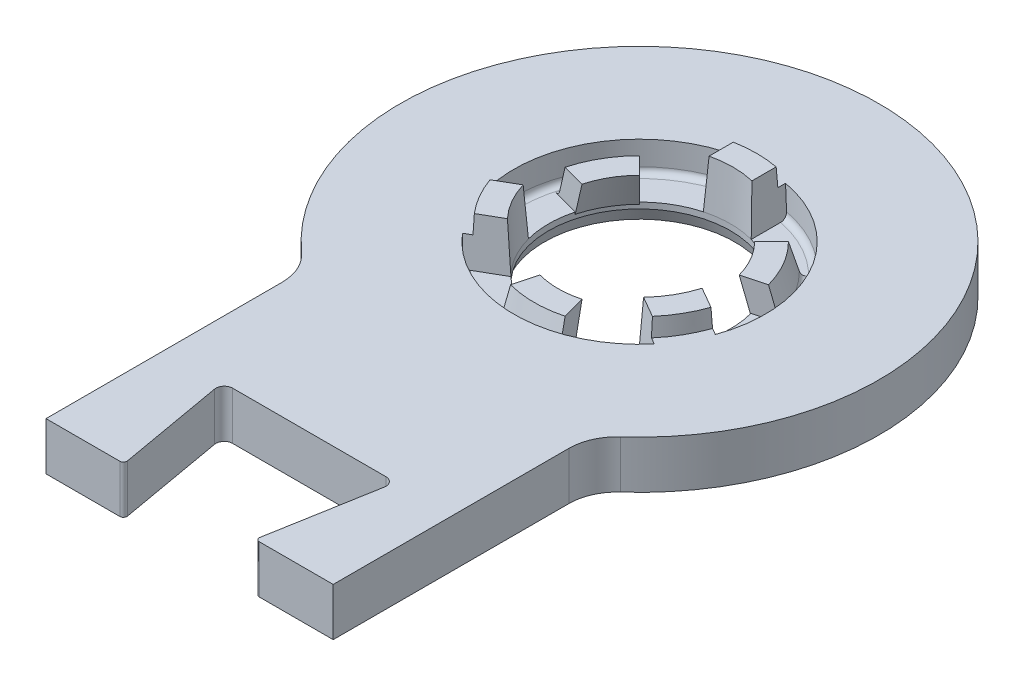
SolidWorks part; units mm, degrees
ref_plane "Front Plane" through (0, 0, 0) normal (0, 0, 1) x (1, 0, 0)
ref_plane "Top Plane" through (0, 0, 0) normal (0, 1, 0) x (1, 0, 0)
ref_plane "Right Plane" through (0, 0, 0) normal (1, 0, 0) x (0, 0, -1)
sketch "Sketch1" plane through (0, 0, 0) normal (0, 1, 0) x (1, 0, 0)
  line L0 (-6, 6) -> (-6, -13.2915)
  line L1 (-6, -19) -> (-2.7023, -19)
  line L2 (6, -19) -> (6, -13.2915)
  line L3 (6, 6) -> (-6, 6)
  line L4 (-6, -13.2915) -> (-6, -19)
  line L5 (6, -13.2915) -> (6, 6)
  line L6 (0, -19) -> (0, 0) construction
  line L7 (-2.6007, -19) -> (-3.5, -13.9) construction
  line L8 (-3.5, -13.9) -> (0, -13.9) construction
  line L9 (-2.7023, -19) -> (-3.6192, -13.8)
  line L10 (-3.6192, -13.8) -> (0, -13.8)
  line L11 (-2.6992, -19.0174) -> (-3.6192, -13.8) construction
  line L12 (2.7023, -19) -> (6, -19)
  line L13 (3.6192, -13.8) -> (0, -13.8)
  line L14 (2.7023, -19) -> (3.6192, -13.8)
  circle A0 centre (0, 0) radius 4
  dimension "D1" = 8
  dimension "D5" = 6
  dimension "D7" = 80
  dimension "D2" = 25
  dimension "D3" = 6
  dimension "D4" = 12
  dimension "D8" = 3.5
  dimension "D9" = 5.1
  dimension "D10" = 0.1
extrude "Boss-Extrude1" add sketch "Sketch1" along normal blind 2
sketch "Sketch2" plane through (0, 0, 0) normal (0, 1, 0) x (1, 0, 0)
  circle A0 centre (0, 0) radius 10
  circle A1 centre (0, 0) radius 3.8
  dimension "D1" = 20
  dimension "D2" = 7.6
extrude "Boss-Extrude2" add sketch "Sketch2" along normal blind 2
sketch "Sketch3" plane through (0, 0, 0) normal (0, -1, 0) x (1, 0, 0)
  line L0 (-3, 0) -> (-3, 4)
  line L1 (3, 0) -> (3, 4)
  arc A0 (-3, 0) -> (3, 0) centre (0, 0) ccw
  arc A1 (-3, 4) -> (3, 4) centre (0, 0) ccw
extrude "Boss-Extrude3" [suppressed] add sketch "Sketch3" along normal blind 4
fillet "Fillet1" [suppressed] radius 0.5
fillet "Fillet2" [suppressed] radius 1
sketch "Sketch4" plane through (0, 2, 0) normal (0, 1, 0) x (1, 0, 0)
  line L0 (-6, -8) -> (-6, -19) construction
  line L1 (-6, -18.8) -> (6, -18.8)
  line L2 (-6, -18.8) -> (-6, -19)
  line L3 (-6, -19) -> (6, -19)
  line L4 (6, -18.8) -> (6, -19)
  dimension "D1" = 0.2
extrude "Cut-Extrude1" cut sketch "Sketch4" against normal blind 4
fillet "Fillet3" radius 0.35 2 edges at (3.6192, 1, 13.8) (-3.6192, 1, 13.8)
fillet "Fillet4" radius 0.15 2 edges at (2.7375, 1, 18.8) (-2.7375, 1, 18.8)
sketch "Sketch5" plane through (0, 0, 0) normal (0, 1, 0) x (1, 0, 0)
  circle A1 centre (0, 0) radius 3
  circle A2 centre (0, 0) radius 2.1
  dimension "D1" = 4.2
  dimension "D2" = 6
extrude "Boss-Extrude4" [suppressed] add sketch "Sketch5" along normal blind 13
fillet "Fillet5" [suppressed] radius 2
fillet "Fillet6" radius 2 2 edges at (-6, 1, 8) (6, 1, 8)
sketch "Sketch6" plane through (0, 2, 0) normal (0, 1, 0) x (1, 0, 0)
  circle A0 centre (0, 0) radius 3.5
  dimension "D1" = 7
extrude "Boss-Extrude5" [suppressed] add sketch "Sketch6" along normal blind 2 contours A0
sketch "Sketch7" [suppressed] plane through (0, 4, 0) normal (0, 1, 0) x (1, 0, 0)
  circle A0 centre (0, 0) radius 3.15
extrude "Cut-Extrude3" [suppressed] cut sketch "Sketch7" against normal blind 3.2
fillet "Fillet7" [suppressed] radius 2
fillet "Fillet8" [suppressed] radius 1
fillet "Fillet9" [suppressed] radius 0.1
sketch "Sketch8" plane through (0, 2, 0) normal (0, 1, 0) x (1, 0, 0)
  line L0 (0, 0) -> (0, 3.9) construction
  line L1 (-0.5, 3.65) -> (0, 2.65)
  line L2 (-0.5, 4.15) -> (0.5, 4.15)
  line L3 (-0.5, 4.15) -> (-0.5, 3.65)
  line L4 (-0.5, 3.65) -> (0.5, 3.65) construction
  line L5 (0.5, 4.15) -> (0.5, 3.65)
  line L6 (-0.5, 4.15) -> (0.5, 3.65) construction
  line L7 (-0.5, 3.65) -> (0.5, 4.15) construction
  line L8 (0, 2.65) -> (0.5, 3.65)
  dimension "D1" = 3.9
  dimension "D2" = 0.5
  dimension "D3" = 1
  dimension "D4" = 1
extrude "Boss-Extrude6" [suppressed] add sketch "Sketch8" against normal blind 2
pattern_circular "CirPattern1" [suppressed] count 5 over 360
sketch "Sketch11" plane through (0, 2, 0) normal (0, 1, 0) x (1, 0, 0)
  circle A0 centre (0, 0) radius 4
  circle A1 centre (0, 0) radius 5
  dimension "D1" = 8
  dimension "D2" = 10
extrude "Boss-Extrude7" [suppressed] add sketch "Sketch11" along normal blind 2 draft 3
sketch "Sketch13" plane through (0, 2, 0) normal (0, 1, 0) x (1, 0, 0)
  circle A0 centre (0, 0) radius 5 construction
  circle A1 centre (0, 0) radius 5.25
  dimension "D1" = 10
  dimension "D2" = 10.5
extrude "Cut-Extrude5" cut sketch "Sketch13" against normal blind 1.25
fillet "Fillet10" [suppressed] radius 0.2
sketch "Sketch12" plane through (0, 0, 0) normal (1, 0, 0) x (0, 0, -1)
  line L0 (0, 0) -> (-4, 0) construction
  line L1 (-7.4536, 0) -> (10, 0) construction
  line L2 (-3.8, 0) -> (3.8, 0) construction
  line L3 (0, 0) -> (0, 2) construction
  line L4 (3.8, 2) -> (-3.8, 2) construction
  line L5 (-4, 0) -> (-3.4, 2)
  line L6 (-3.4, 2) -> (-4.4, 2)
  line L7 (-4.4, 2) -> (-5, 0)
  line L8 (-5, 0) -> (-4, 0)
  line L9 (-4, 0) -> (-4.0344, -0.0135)
  dimension "D1" = 0
  dimension "D2" = 3.4
  dimension "D3" = 1
  dimension "D4" = 4
revolve "Revolve2" add sketch "Sketch12" angle 30 mid plane about L3
pattern_circular "CirPattern2" count 3 over 360 about axis through (0, 0, 0) along (0, 1, 0) of "Revolve2"
chamfer "Chamfer1" distance 0.5 angle 20 1 edges at (0, 0, 3.8)
fillet "Fillet13" [suppressed] radius 0.25
fillet "Fillet14" radius 0.25 4 edges at (0, 0.75, 5.25) (-4.1353, 0.75, -2.3875) (4.1353, 0.75, -2.3875) (0, 0.75, 4.775)
sketch "Sketch15" plane through (0, 0, 0) normal (0, -1, 0) x (1, 0, 0)
  line L2 (1, -4.899) -> (1, -3.6661)
  line L4 (-1, -4.899) -> (-1, -3.6661)
  arc A0 (-1, -3.6661) -> (1, -3.6661) centre (0, 0) ccw
  arc A1 (-1, -4.899) -> (1, -4.899) centre (0, 0) ccw
  point P4 (0, -5)
  dimension "D1" = 7.6
  dimension "D2" = 10
  dimension "D3" = 1
  dimension "D4" = 1
extrude "Boss-Extrude8" add sketch "Sketch15" against normal blind 2 draft 3 from offset 0.75 offset against normal yes
sketch "Sketch16" plane through (0, 0.75, 0) normal (0, 1, 0) x (1, 0, 0)
  line L0 (-1, 3.6661) -> (-1, 4.899) construction
  line L1 (1, 6.2175) -> (-1, 6.2175)
  line L2 (1, 6.2175) -> (1, 4.2825)
  line L3 (1, 4.2825) -> (-1, 4.2825)
  line L4 (-1, 6.2175) -> (-1, 4.2825)
  line L5 (1, 6.2175) -> (-1, 4.2825) construction
  line L6 (1, 4.2825) -> (-1, 6.2175) construction
  circle A0 centre (0, 0) radius 5.25 construction
  circle A1 centre (0, 0) radius 5.25 construction
  point P0 (0, 5.25)
extrude "Boss-Extrude9" add sketch "Sketch16" along normal blind 1.25 draft 3
pattern_circular "CirPattern3" count 3 over 360 about axis through (0, 0, 0) along (0, 1, 0) of "Boss-Extrude8", "Boss-Extrude9"
fillet "Fillet15" [suppressed] radius 0.25
